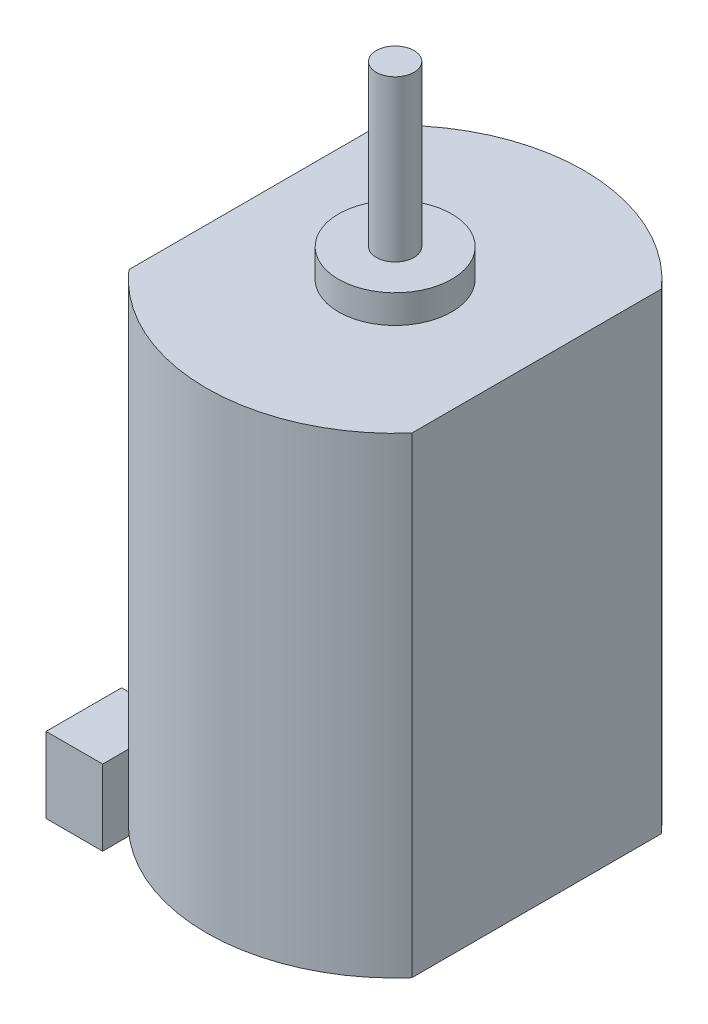
SolidWorks part; units mm, degrees
ref_plane "前视基准面" through (0, 0, 0) normal (0, 0, 1) x (1, 0, 0)
ref_plane "上视基准面" through (0, 0, 0) normal (0, 1, 0) x (1, 0, 0)
ref_plane "右视基准面" through (0, 0, 0) normal (1, 0, 0) x (0, 0, -1)
sketch "草图1" plane through (0, 0, 0) normal (0, 1, 0) x (1, 0, 0)
  circle A0 centre (0, 0) radius 10
  dimension "D1" = 20
extrude "圆柱凸台-拉伸1" add sketch "草图1" along normal blind 25
sketch "草图2" plane through (0, 0, 0) normal (0, -1, 0) x (1, 0, 0)
  line L0 (0, 0) -> (0, 8.2637) construction
  line L2 (-7.5, 10) -> (-7.5, -10)
  line L4 (7.5, 10) -> (7.5, -10)
  line L5 (7.5, 10) -> (10, 10)
  line L6 (-10, 10) -> (-7.5, 10)
  line L7 (-10, 10) -> (-10, -10)
  line L8 (-10, -10) -> (-7.5, -10)
  line L9 (10, 10) -> (10, -10)
  line L10 (7.5, -10) -> (10, -10)
  circle A0 centre (0, 0) radius 10 construction
  dimension "D1" = 15
extrude "2边切除切除-拉伸1" cut sketch "草图2" against normal up to next
sketch "草图3" plane through (0, 25, 0) normal (0, 1, 0) x (1, 0, 0)
  circle A0 centre (0, 0) radius 3
  dimension "D1" = 6
extrude "前转凸台-拉伸2" add sketch "草图3" along normal blind 1.5
sketch "草图4" plane through (0, 26.5, 0) normal (0, 1, 0) x (1, 0, 0)
  circle A0 centre (0, 0) radius 1
  dimension "D1" = 2
extrude "前转杆凸台-拉伸3" add sketch "草图4" along normal blind 10 from surface at -1.5 starting at face at (0, 25, 3)
sketch "草图5" plane through (0, 0, 0) normal (0, -1, 0) x (1, 0, 0)
  line L2 (4, 3) -> (4, -3)
  arc A0 (4, 3) -> (4, -3) centre (0, 0) ccw
  dimension "D1" = 10
  dimension "D2" = 4
extrude "后转凸台-拉伸4" add sketch "草图5" along normal blind 27.3 from surface at -25 starting at face at (0, 25, 3)
sketch "草图6" plane through (0, -2.3, 0) normal (0, -1, 0) x (1, 0, 0)
  circle A1 centre (0, 0) radius 1
  dimension "D1" = 2
extrude "后转杆凸台-拉伸5" add sketch "草图6" along normal blind 1
sketch "草图7" plane through (-7.5, 0, 0) normal (-1, 0, 0) x (0, 0, 1)
  line L1 (-8, 3) -> (-4, 3)
  line L2 (-8, 3) -> (-8, -1)
  line L3 (-8, -1) -> (-4, -1)
  line L4 (8, 3) -> (8, -1)
  line L5 (0, 0) -> (0, 3) construction
  line L6 (-6.6144, 0) -> (6.6144, 0) construction
  line L7 (4, 3) -> (8, 3)
  line L9 (-4, 3) -> (-4, -1)
  line L11 (4, 3) -> (4, -1)
  line L12 (4, -1) -> (8, -1)
  dimension "D1" = 16
  dimension "D2" = 4
  dimension "D3" = 3
  dimension "D4" = 4
extrude "引线凸台-拉伸6" add sketch "草图7" along normal blind 3
